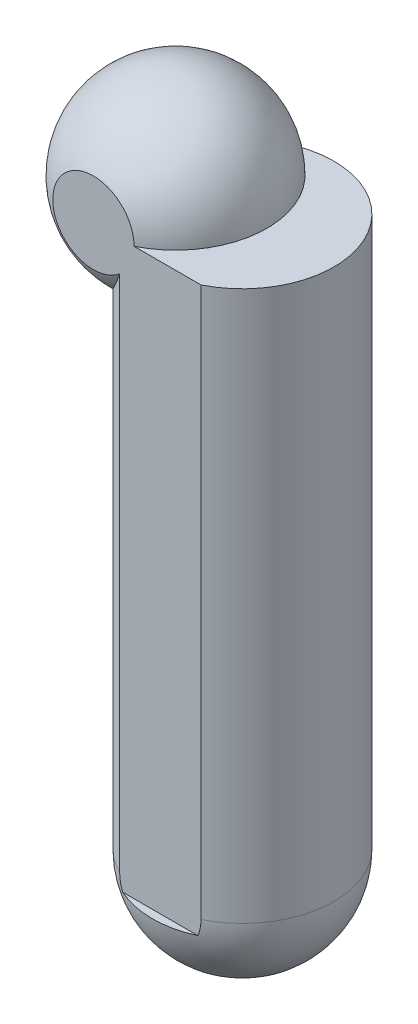
SolidWorks part; units mm, degrees
ref_plane "Front Plane" through (0, 0, 0) normal (0, 0, 1) x (1, 0, 0)
ref_plane "Top Plane" through (0, 0, 0) normal (0, 1, 0) x (1, 0, 0)
ref_plane "Right Plane" through (0, 0, 0) normal (1, 0, 0) x (0, 0, -1)
sketch "Sketch1" plane through (0, 0, 0) normal (0, 1, 0) x (1, 0, 0)
  circle A0 centre (0, 0) radius 50
  dimension "D1" = 100
extrude "Boss-Extrude1" add sketch "Sketch1" along normal blind 300
sketch "Sketch2" plane through (0, 0, 0) normal (0, 0, 1) x (1, 0, 0)
  line L0 (50, 300) -> (-50, 300) construction
  line L1 (-36.5268, 250) -> (-36.5268, 350)
  arc A0 (-36.5268, 250) -> (-36.5268, 350) centre (-36.5268, 300) ccw
  dimension "D1" = 100
revolve "Revolve1" add sketch "Sketch2" angle 360 about L1
sketch "Sketch3" plane through (0, 0, 0) normal (0, 0, 1) x (1, 0, 0)
  line L0 (0, -50) -> (0, 50)
  arc A0 (0, -50) -> (0, 50) centre (0, 0) ccw
revolve "Revolve2" add sketch "Sketch3" angle 360 about L0
sketch "Sketch4" plane through (0, 0, 0) normal (0, 0, 1) x (1, 0, 0)
  line L1 (-59.7767, 247.9141) -> (-47.1796, 247.9141)
  line L2 (-59.7767, 247.9141) -> (-59.7767, -31.5132)
  line L3 (-59.7767, -31.5132) -> (-47.1796, -31.5132)
  line L4 (-47.1796, 247.9141) -> (-47.1796, -31.5132)
  dimension "D1" = 279.4273
  dimension "D2" = 12.5971
extrude "Cut-Extrude1" cut sketch "Sketch4" against normal through all both and the other way through all
sketch "Sketch5" plane through (0, 0, 0) normal (1, 0, 0) x (0, 0, -1)
  line L1 (-58.7586, -8.4346) -> (-44.8088, -8.4346)
  line L2 (-58.7586, -8.4346) -> (-58.7586, 355.3262)
  line L3 (-58.7586, 355.3262) -> (-44.8088, 355.3262)
  line L4 (-44.8088, -8.4346) -> (-44.8088, 355.3262)
  dimension "D1" = 363.7608
  dimension "D2" = 13.9498
extrude "Cut-Extrude2" cut sketch "Sketch5" against normal through all both and the other way through all
